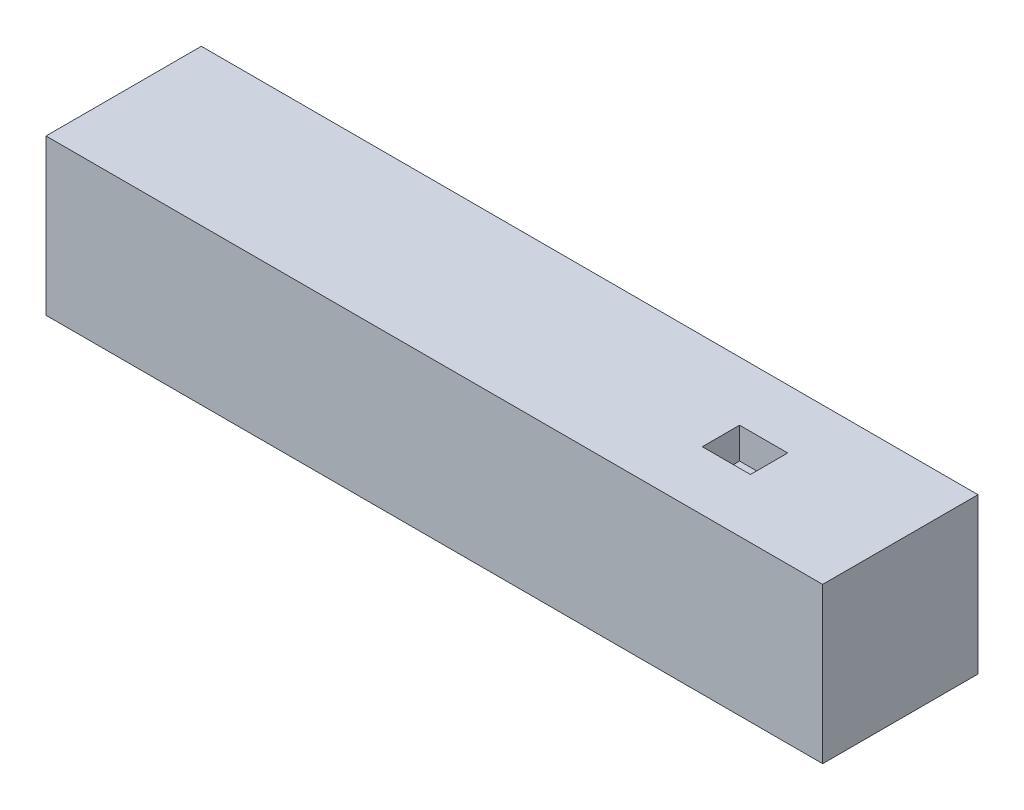
SolidWorks part; units mm, degrees
ref_plane "Front Plane" through (0, 0, 0) normal (0, 0, 1) x (1, 0, 0)
ref_plane "Top Plane" through (0, 0, 0) normal (0, 1, 0) x (1, 0, 0)
ref_plane "Right Plane" through (0, 0, 0) normal (1, 0, 0) x (0, 0, -1)
sketch "Sketch1" plane through (0, 0, 0) normal (0, 1, 0) x (1, 0, 0)
  line L1 (-25, -5) -> (25, -5)
  line L2 (-25, -5) -> (-25, 5)
  line L3 (-25, 5) -> (25, 5)
  line L4 (25, -5) -> (25, 5)
  line L5 (-25, -5) -> (25, 5) construction
  line L6 (-25, 5) -> (25, -5) construction
  point P0 (0, 0)
  dimension "D1" = 50
  dimension "D2" = 10
extrude "Boss-Extrude1" add sketch "Sketch1" along normal blind 10
sketch "Sketch2" plane through (0, 10, 0) normal (0, 1, 0) x (1, 0, 0)
  line L1 (13.45, -1.2) -> (16.55, -1.2)
  line L2 (13.45, -1.2) -> (13.45, 1.2)
  line L3 (13.45, 1.2) -> (16.55, 1.2)
  line L4 (16.55, -1.2) -> (16.55, 1.2)
  line L5 (13.45, -1.2) -> (16.55, 1.2) construction
  line L6 (13.45, 1.2) -> (16.55, -1.2) construction
  line L7 (25, -5) -> (25, 5) construction
  line L8 (0, 0) -> (25, 0) construction
  point P0 (15, 0)
  point P10 (0, 0)
  dimension "D1" = 3.1
  dimension "D2" = 2.4
  dimension "D4" = 10
extrude "Cut-Extrude1" cut sketch "Sketch2" against normal blind 2
